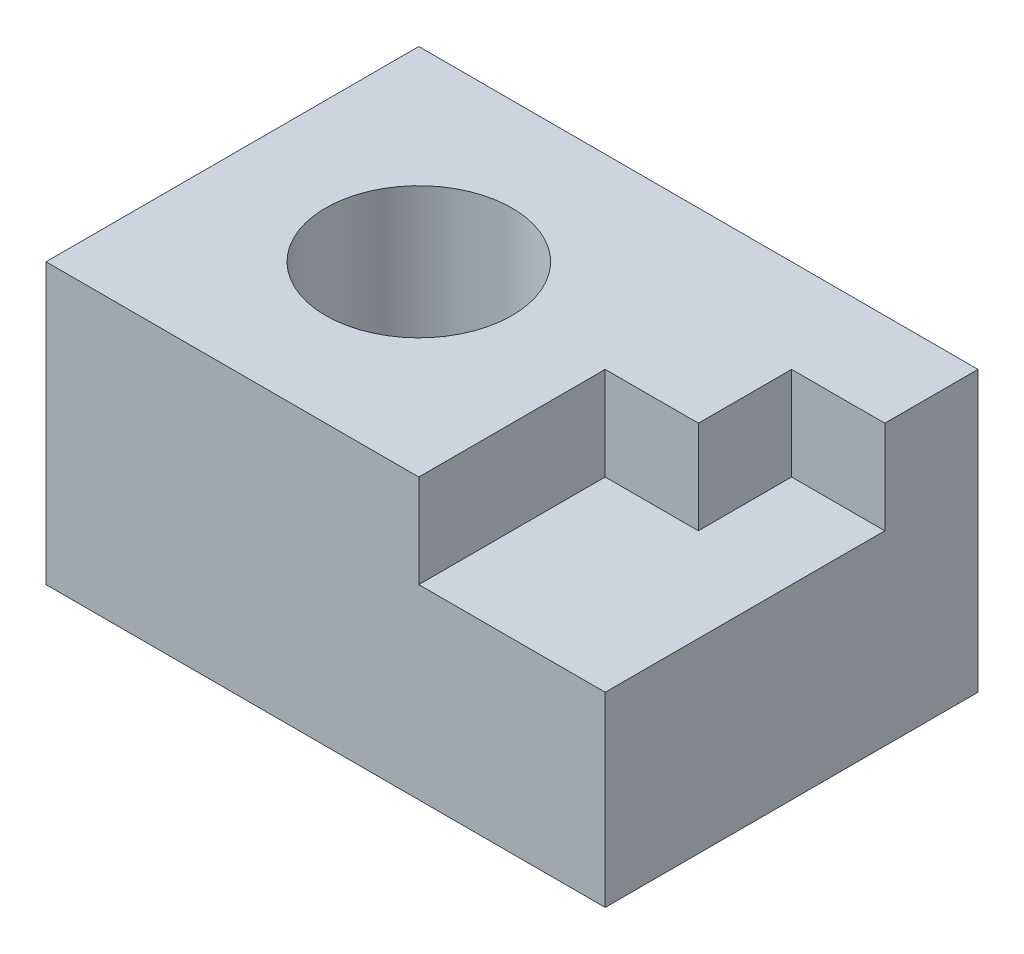
SolidWorks part; units mm, degrees
ref_plane "Front Plane" through (0, 0, 0) normal (0, 0, 1) x (1, 0, 0)
ref_plane "Top Plane" through (0, 0, 0) normal (0, 1, 0) x (1, 0, 0)
ref_plane "Right Plane" through (0, 0, 0) normal (1, 0, 0) x (0, 0, -1)
sketch "Sketch1" plane through (0, 0, 0) normal (0, 1, 0) x (1, 0, 0)
  line L1 (0, 0) -> (152.4, 0)
  line L2 (0, 0) -> (0, 101.6)
  line L3 (0, 101.6) -> (152.4, 101.6)
  line L4 (152.4, 0) -> (152.4, 101.6)
  dimension "D1" = 152.4
  dimension "D2" = 101.6
extrude "Boss-Extrude1" add sketch "Sketch1" along normal blind 76.2 contours L3 L4 L1 L2
sketch "Sketch2" plane through (0, 76.2, 0) normal (0, 1, 0) x (1, 0, 0)
  line L0 (101.6, 0) -> (101.6, 50.8)
  line L1 (0, 0) -> (152.4, 0) construction
  line L2 (101.6, 50.8) -> (127, 50.8)
  line L3 (127, 50.8) -> (127, 76.2)
  line L4 (127, 76.2) -> (152.4, 76.2)
  line L5 (152.4, 0) -> (152.4, 101.6) construction
  line L6 (0, 0) -> (0, 101.6) construction
  line L7 (101.6, 0) -> (152.4, 0)
  line L8 (152.4, 0) -> (152.4, 76.2)
  dimension "D1" = 101.6
  dimension "D2" = 25.4
  dimension "D3" = 25.4
  dimension "D4" = 50.8
extrude "Cut-Extrude3" cut sketch "Sketch2" against normal blind 25.4
sketch "Sketch3" plane through (0, 76.2, 0) normal (0, 1, 0) x (1, 0, 0)
  line L0 (0, 0) -> (0, 101.6) construction
  line L1 (0, 101.6) -> (152.4, 101.6) construction
  circle A0 centre (50.8, 50.8) radius 25.4
  point P4 (0, 0)
  dimension "D1" = 50.8
  dimension "D2" = 50.8
  dimension "D3" = 50.8
extrude "Cut-Extrude4" cut sketch "Sketch3" against normal through all
